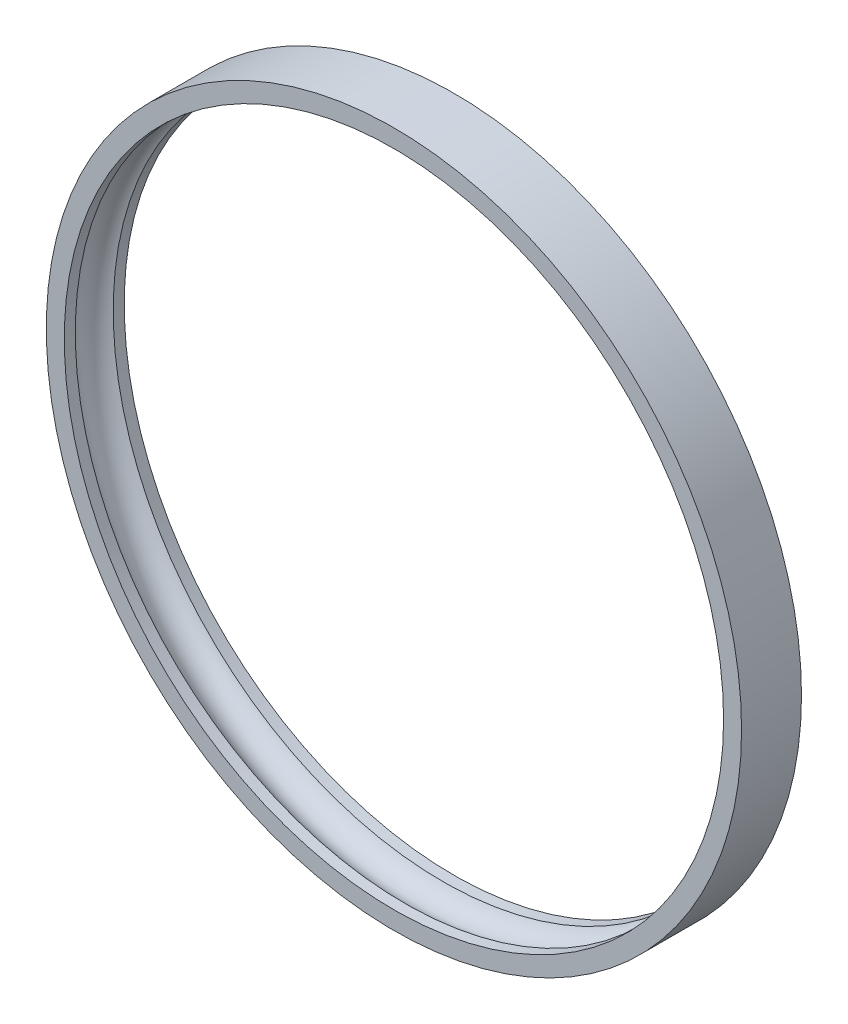
SolidWorks part; units mm, degrees
ref_plane "Front Plane" through (0, 0, 0) normal (0, 0, 1) x (1, 0, 0)
ref_plane "Top Plane" through (0, 0, 0) normal (0, 1, 0) x (1, 0, 0)
ref_plane "Right Plane" through (0, 0, 0) normal (1, 0, 0) x (0, 0, -1)
sketch "Sketch2" plane through (0, 0, 0) normal (1, 0, 0) x (0, 0, -1)
  line L9 (0, 0) -> (0, -110) construction
  line L10 (0, -110) -> (36.6658, -110) construction
  line L11 (36.6658, -110) -> (18.3329, -110) construction
  line L12 (-46.6891, -10) -> (86.0472, -10) construction
  line L13 (-10, 6) -> (10, 6)
  line L14 (10, 6) -> (10, 0)
  line L15 (-10, 6) -> (-10, 0)
  line L18 (0, -8) -> (0, -3) construction
  line L20 (-10, 0) -> (-6.3246, 0)
  line L21 (6.3246, 0) -> (10, 0)
  arc A6 (6.3246, 0) -> (-6.3246, 0) centre (0, -3) ccw
  dimension "D4" = 10
  dimension "D2" = 5
  dimension "D1" = 20
  dimension "D3" = 6
  dimension "D6" = 100
revolve "Revolve2" add sketch "Sketch2" angle 360 about L10
